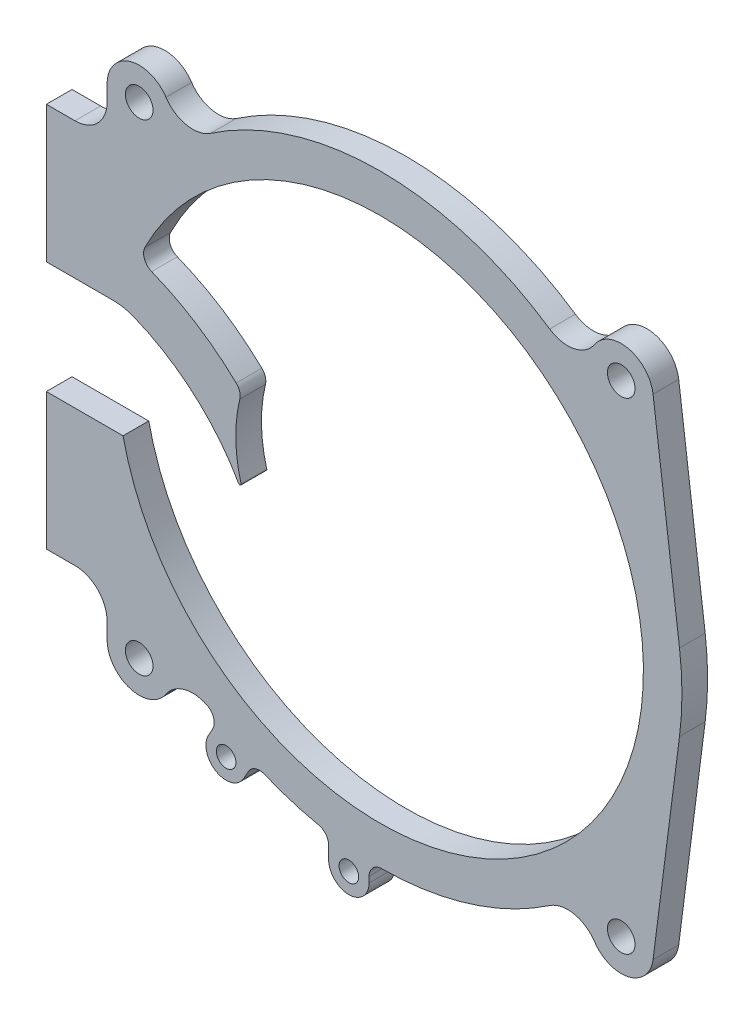
SolidWorks part; units mm, degrees
material "Thornel Mat VMA"
ref_plane "前视基准面" through (0, 0, 0) normal (0, 0, 1) x (1, 0, 0)
ref_plane "上视基准面" through (0, 0, 0) normal (0, 1, 0) x (1, 0, 0)
ref_plane "右视基准面" through (0, 0, 0) normal (1, 0, 0) x (0, 0, -1)
sketch "草图1" plane through (0, 0, 0) normal (0, 0, 1) x (1, 0, 0)
  line L0 (0, 0) -> (50000, 0) construction
  line L1 (-52, 8.75) -> (-52, -8.75) construction
  line L2 (-52, 8.75) -> (-52, 30)
  line L3 (-52, -8.75) -> (-52, -30)
  line L4 (-52, 8.75) -> (-40.0554, 8.75)
  line L5 (-52, -8.75) -> (-40.0554, -8.75)
  line L6 (-42.54, 37.5) -> (-42.54, 35)
  line L7 (-47.54, 30) -> (-52, 30)
  line L8 (-47.54, -30) -> (-52, -30)
  line L9 (-42.54, -37.5) -> (-42.54, -35)
  line L10 (0, 0) -> (0, -50000) construction
  line L11 (42.4995, 38.1352) -> (46.6192, 5.9711)
  line L12 (42.4995, -38.1352) -> (46.6192, -5.9711)
  arc A0 (-40.0554, -8.75) -> (-37.5934, 16.3627) centre (0, 0) ccw
  arc A1 (-40.0554, 8.75) -> (-40.0554, -8.75) centre (0, 0) ccw construction
  circle A2 centre (-37.54, 37.5) radius 2.15
  circle A3 centre (-37.54, -37.5) radius 2.15
  arc A4 (-33.3722, 40.2622) -> (-42.54, 37.5) centre (-37.54, 37.5) ccw
  arc A5 (-42.54, -37.5) -> (-33.3722, -40.2622) centre (-37.54, -37.5) ccw
  arc A6 (-26.3963, -38.8874) -> (26.3963, -38.8874) centre (0, 0) ccw
  arc A7 (-33.3722, 40.2622) -> (-26.3963, 38.8874) centre (-29.2045, 43.0244) ccw
  arc A8 (-33.3722, -40.2622) -> (-42.54, -37.5) centre (-37.54, -37.5) cw
  arc A9 (-33.3722, -40.2622) -> (-26.3963, -38.8874) centre (-29.2045, -43.0244) cw
  circle A10 centre (37.54, -37.5) radius 2.15
  circle A11 centre (37.54, 37.5) radius 2.15
  arc A12 (42.4995, 38.1352) -> (33.3722, 40.2622) centre (37.54, 37.5) ccw
  arc A13 (33.3722, -40.2622) -> (42.4995, -38.1352) centre (37.54, -37.5) ccw
  arc A14 (33.3722, 40.2622) -> (26.3963, 38.8874) centre (29.2045, 43.0244) cw
  arc A15 (33.3722, -40.2622) -> (26.3963, -38.8874) centre (29.2045, -43.0244) ccw
  arc A16 (26.3963, 38.8874) -> (-26.3963, 38.8874) centre (0, 0) ccw
  arc A17 (46.6192, -5.9711) -> (46.6192, 5.9711) centre (0, 0) ccw
  arc A18 (-47.54, -30) -> (-42.54, -35) centre (-47.54, -35) cw
  arc A19 (-42.54, 35) -> (-47.54, 30) centre (-47.54, 35) cw
  circle A20 centre (0, 0) radius 22.5 construction
  arc A21 (-40.0554, 8.75) -> (-20.5735, -9.1093) centre (-50.748, -22.4697) cw
  arc A22 (-20.5735, -9.1093) -> (-21.5855, 6.3495) centre (0, 0) cw
  arc A23 (-37.5934, 16.3627) -> (-21.5855, 6.3495) centre (-50.748, -22.4697) cw
  point P8 (-52, 0)
  point P44 (-42.54, -30)
  point P47 (-42.54, 30)
  dimension "D1" = 82
  dimension "D5" = 4.3
  dimension "D6" = 75
  dimension "D8" = 10
  dimension "D9" = 94
  dimension "D10" = 5
  dimension "D11" = 10
  dimension "D12" = 5
  dimension "D13" = 5
  dimension "D14" = 5
  dimension "D15" = 45
  dimension "D16" = 33
  dimension "D17" = 41
  dimension "D2" = 17.5
  dimension "D3" = 52
  dimension "D4" = 60
  dimension "D7" = 14.46
extrude "凸台-拉伸1" add sketch "草图1" along normal blind 4
fillet "圆角1" radius 0.2 1 edges at (-20.5735, -9.1093, 2)
fillet "圆角2" radius 2 1 edges at (-21.5855, 6.3495, 2)
fillet "圆角3" radius 2 1 edges at (-37.5934, 16.3627, 2)
fillet "圆角4" radius 8.5 1 edges at (-40.0554, 8.75, 2)
sketch "草图2" plane through (0, 0, 0) normal (0, 0, -1) x (-1, 0, 0)
  line L0 (1.7331, -49.9117) -> (1.7331, -46.968)
  line L1 (8.0331, -49.9117) -> (8.0331, -46.3084)
  line L2 (21.2341, -45.5418) -> (19.6761, -42.6832)
  line L3 (26.7659, -42.5269) -> (25.2078, -39.6682)
  line L4 (0, 0) -> (24, -44.0343) construction
  circle A0 centre (24, -44.0343) radius 1.525
  circle A1 centre (4.8831, -49.9117) radius 1.525
  arc A2 (21.2341, -45.5418) -> (26.7659, -42.5269) centre (24, -44.0343) ccw
  arc A3 (1.7331, -49.9117) -> (8.0331, -49.9117) centre (4.8831, -49.9117) ccw
  arc A4 (-26.3963, -38.8874) -> (26.3963, -38.8874) centre (0, 0) ccw construction
  arc A5 (1.7331, -46.968) -> (8.0331, -46.3084) centre (0, 0) ccw
  arc A6 (19.6761, -42.6832) -> (25.2078, -39.6682) centre (0, 0) ccw
  point P19 (19.6761, -42.6832)
  dimension "D1" = 3.05
  dimension "D2" = 6.3
  dimension "D3" = 20
  dimension "D4" = 24
extrude "凸台-拉伸2" add sketch "草图2" against normal up to surface (4 mm away) up to face at (-15.9275, 1.1058, 4)
fillet "圆角5" radius 2 4 edges at (-1.7331, -46.968, 2) (-19.6761, -42.6832, 2) (-25.2078, -39.6682, 2) (-8.0331, -46.3084, 2)
